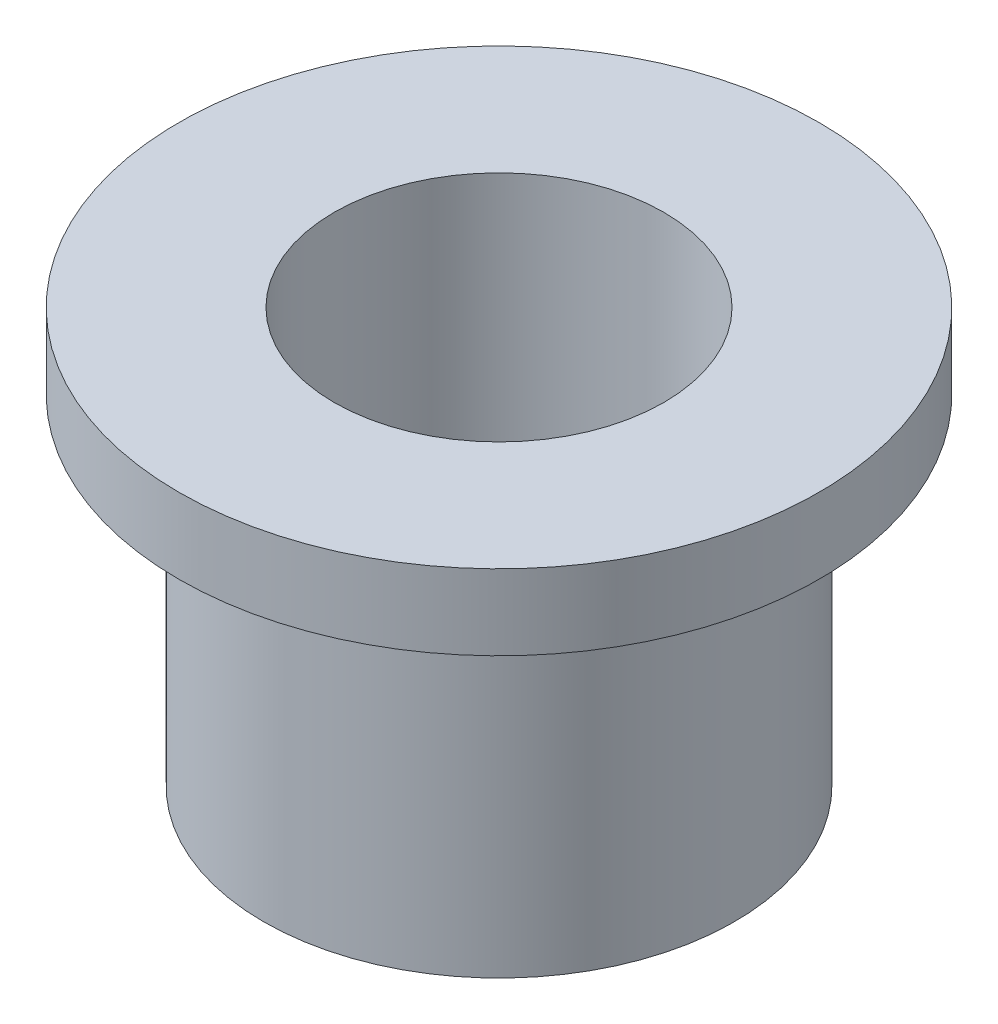
SolidWorks part; units mm, degrees
ref_plane "Front Plane" through (0, 0, 0) normal (0, 0, 1) x (1, 0, 0)
ref_plane "Top Plane" through (0, 0, 0) normal (0, 1, 0) x (1, 0, 0)
ref_plane "Right Plane" through (0, 0, 0) normal (1, 0, 0) x (0, 0, -1)
sketch "Sketch1" plane through (0, 0, 0) normal (0, 0, 1) x (1, 0, 0)
  line L0 (0, 24.1579) -> (0, -30.3216) construction
  line L1 (0, 0) -> (34, 0)
  line L2 (34, 0) -> (34, -8)
  line L3 (34, -8) -> (25, -8)
  line L4 (25, -8) -> (25, -44)
  line L5 (25, -44) -> (0, -44)
  line L6 (0, -44) -> (0, 0)
  line L7 (17.5, 0) -> (17.5, -44)
  point P11 (0, 0)
  dimension "D1" = 34
  dimension "D2" = 8
  dimension "D3" = 44
  dimension "D4" = 25
  dimension "D5" = 17.5
revolve "Revolve1" add sketch "Sketch1" angle 360 about L0
